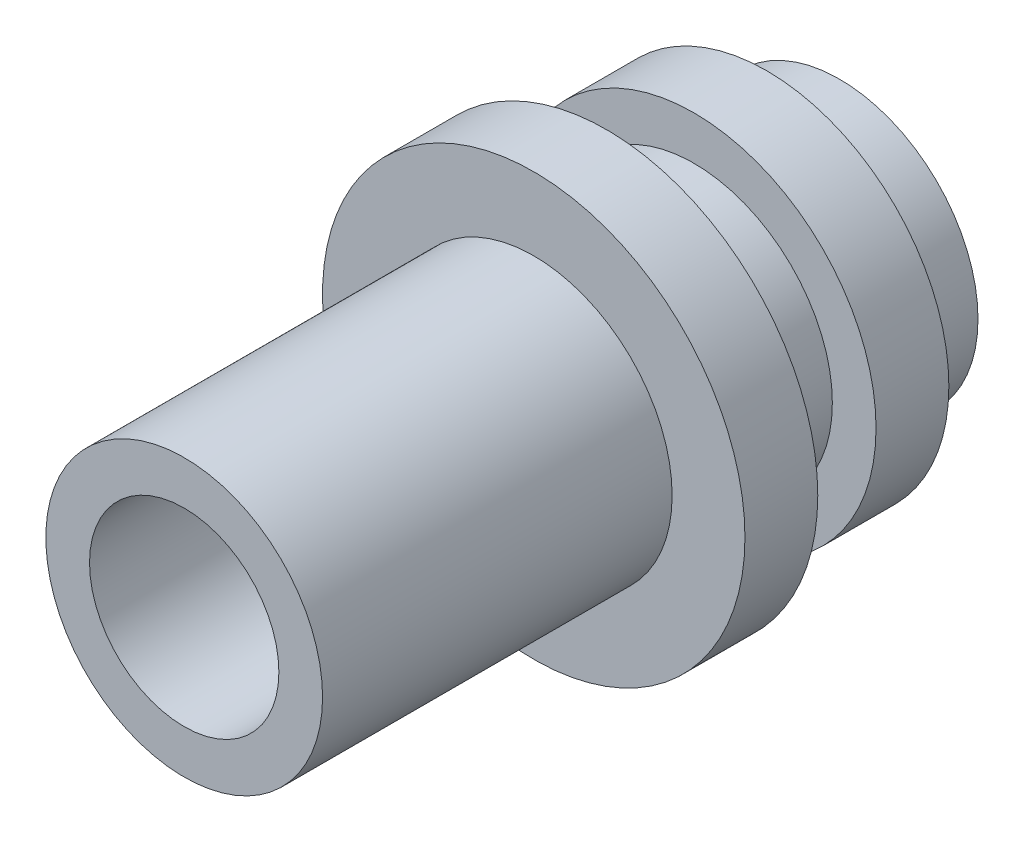
SolidWorks part; units mm, degrees
material "Brass"
ref_plane "Front Plane" through (0, 0, 0) normal (0, 0, 1) x (1, 0, 0)
ref_plane "Top Plane" through (0, 0, 0) normal (0, 1, 0) x (1, 0, 0)
ref_plane "Right Plane" through (0, 0, 0) normal (1, 0, 0) x (0, 0, -1)
other "Configuration Table"
sketch "Sketch1" plane through (0, 0, 0) normal (0, 0, 1) x (1, 0, 0)
  circle A0 centre (0, 0) radius 7.25
  dimension "D1" = 14.5
extrude "Flange" add sketch "Sketch1" along normal blind 2.5
sketch "Sketch2" plane through (0, 0, 0) normal (0, 0, 1) x (1, 0, 0)
  circle A0 centre (0, 0) radius 4.75
  dimension "D1" = 9.5
extrude "Barrel" add sketch "Sketch2" along normal blind 12 from offset 2.5
sketch "Sketch3" plane through (0, 0, 0) normal (0, 0, 1) x (1, 0, 0)
  circle A0 centre (0, 0) radius 4.75
  dimension "D1" = 9.5
extrude "Rear_Thread" add sketch "Sketch3" along normal blind 8 from offset 8
sketch "Sketch4" plane through (0, 0, 0) normal (0, 0, 1) x (1, 0, 0)
  circle A0 centre (0, 0) radius 6.25
  dimension "D1" = 12.5
extrude "Rear_Nut" add sketch "Sketch4" along normal blind 2.5 from offset 5.5
sketch "Sketch5" plane through (0, 0, 0) normal (0, 0, 1) x (1, 0, 0)
  circle A0 centre (0, 0) radius 3.25
  dimension "D1" = 6.5
extrude "Socket_Bore" cut sketch "Sketch5" against normal blind 8 from offset 14.5
equation "\"Jar_OD\"= 90  'ASSUMED - Part G fallback - jar outer diameter"
equation "\"Jar_H\"= 120  'ASSUMED - Part G fallback - jar height"
equation "\"Pump_L\"= 45  'ASSUMED - Part G fallback"
equation "\"Pump_W\"= 24  'ASSUMED - Part G fallback"
equation "\"Pump_H\"= 33  'ASSUMED - Part G fallback"
equation "\"Pump_Outlet_OD\"= 7.5  'ASSUMED - Part G fallback"
equation "\"Tube_OD\"= 8  'ASSUMED - Part G fallback"
equation "\"Tube_ID\"= 6  'ASSUMED - Part G fallback"
equation "\"TDS_Body_Dia\"= 12  'ASSUMED - Part G fallback"
equation "\"TDS_Wet_Len\"= 45  'ASSUMED - Part G fallback - length in water"
equation "\"DS_Tube_Dia\"= 6  'ASSUMED - Part G fallback"
equation "\"DS_Tube_Len\"= 50  'ASSUMED - Part G fallback"
equation "\"ORP_Body_Dia\"= 12  'ASSUMED - Part G fallback"
equation "\"ORP_Body_Len\"= 150  'ASSUMED - Part G fallback"
equation "\"ORP_Cap_Dia\"= 16  'ASSUMED - Part G fallback"
equation "\"Turb_W\"= 33  'ASSUMED - Part G fallback - head width"
equation "\"Turb_D\"= 28  'ASSUMED - Part G fallback - head depth"
equation "\"Turb_H\"= 30  'ASSUMED - Part G fallback - head height"
equation "\"Turb_Slot_W\"= 10  'ASSUMED - Part G fallback - slot width"
equation "\"Flow_L\"= 62  'ASSUMED - Part G fallback YF-S201"
equation "\"Flow_W\"= 36  'ASSUMED - Part G fallback"
equation "\"Flow_H\"= 35  'ASSUMED - Part G fallback"
equation "\"Thread_G12_OD\"= 20.955  'ASSUMED - Part G fallback thread G1/2 (major diameter)"
equation "\"Valve_L\"= 75  'ASSUMED - Part G fallback"
equation "\"Valve_W\"= 45  'ASSUMED - Part G fallback"
equation "\"Valve_H\"= 60  'ASSUMED - Part G fallback"
equation "\"Tee_L\"= 40  'ASSUMED - Part G fallback - overall length"
equation "\"Tee_Branch_L\"= 25  'ASSUMED - Part G fallback"
equation "\"Tee_OD\"= 12  'ASSUMED - Part G fallback"
equation "\"Cuv_W\"= 12.5  'ASSUMED - old R3 cuvette (station suppressed in SS4)"
equation "\"Cuv_D\"= 12.5  'ASSUMED - old R3 cuvette (station suppressed in SS4)"
equation "\"Cuv_H\"= 45  'ASSUMED - old R3 cuvette (station suppressed in SS4)"
equation "\"LED_Board_L\"= 20  'ASSUMED - Part G fallback"
equation "\"LED_Board_W\"= 20  'ASSUMED - Part G fallback - LED at centre"
equation "\"GUVA_L\"= 20  'ASSUMED - Part G fallback"
equation "\"GUVA_W\"= 12  'ASSUMED - Part G fallback - sensor at centre"
equation "\"Reed_L\"= 27  'ASSUMED - Part G fallback MC-38 half"
equation "\"Reed_W\"= 14  'ASSUMED - Part G fallback"
equation "\"Reed_H\"= 8  'ASSUMED - Part G fallback"
equation "\"ESP_L\"= 51  'ASSUMED - Part G fallback"
equation "\"ESP_W\"= 28  'ASSUMED - Part G fallback"
equation "\"TFT_L\"= 58  'ASSUMED - Part G fallback - board"
equation "\"TFT_W\"= 35  'ASSUMED - Part G fallback - board"
equation "\"TFT_Win_L\"= 35  'ASSUMED - Part G fallback - visible window"
equation "\"TFT_Win_W\"= 28  'ASSUMED - Part G fallback - visible window"
equation "\"Relay_L\"= 50  'ASSUMED - Part G fallback"
equation "\"Relay_W\"= 26  'ASSUMED - Part G fallback"
equation "\"Relay_H\"= 19  'ASSUMED - Part G fallback"
equation "\"Mosfet_L\"= 34  'ASSUMED - Part G fallback"
equation "\"Mosfet_W\"= 17  'ASSUMED - Part G fallback"
equation "\"Mosfet_H\"= 12  'ASSUMED - Part G fallback"
equation "\"TDS_Board_L\"= 42  'ASSUMED - Part G fallback"
equation "\"TDS_Board_W\"= 32  'ASSUMED - Part G fallback"
equation "\"Turb_Board_L\"= 38  'ASSUMED - Part G fallback"
equation "\"Turb_Board_W\"= 28  'ASSUMED - Part G fallback"
equation "\"BNC_Thread_Dia\"= 9.5  'ASSUMED - Part G fallback"
equation "\"Plate_L\"= 420  'ASSUMED - Part G fallback"
equation "\"Plate_W\"= 297  'ASSUMED - Part G fallback"
equation "\"Plate_T\"= 6  'ASSUMED - Part G fallback"
equation "\"Probe_Clr\"= 0.3  'DESIGN VALUE - Part C rule 3 - printed probe hole = diameter + 0.3"
equation "\"Cuv_Clr\"= 0.2  'DESIGN VALUE - Part C rule 3 - cuvette pocket = size + 0.2"
equation "\"Label_H\"= 0.6  'DESIGN VALUE - Part D - raised label height"
equation "\"D1@Sketch2\" = \"BNC_Thread_Dia\""
equation "\"Booster_L\"= 150  'ASSUMED - Part G fallback - booster pump"
equation "\"Booster_W\"= 95  'ASSUMED - Part G fallback"
equation "\"Booster_H\"= 100  'ASSUMED - Part G fallback"
equation "\"PTube_OD\"= 6.35  'ASSUMED - Part G fallback - product tube 1/4 inch"
equation "\"Qz_Out\"= 12  'ASSUMED - Part G fallback - quartz channel outside square"
equation "\"Qz_Path\"= 10  'ASSUMED - Part G fallback - quartz channel inside light path"
equation "\"Qz_L\"= 40  'ASSUMED - Part G fallback - quartz channel length"
equation "\"LED860_Dia\"= 5  'ASSUMED - Part G fallback - 860 nm LED"
equation "\"BPW_L\"= 5.4  'ASSUMED - Part G fallback - BPW34"
equation "\"BPW_W\"= 4.3  'ASSUMED - Part G fallback - BPW34"
equation "\"Cart_Dia\"= 50  'ASSUMED - Part G fallback - sediment and pre-carbon cartridges"
equation "\"Cart_L\"= 255  'ASSUMED - Part G fallback"
equation "\"UF_Dia\"= 50  'ASSUMED - Part G fallback - UF cartridge"
equation "\"UF_L\"= 260  'ASSUMED - Part G fallback"
equation "\"RO_Dia\"= 62  'ASSUMED - Part G fallback - RO membrane housing"
equation "\"RO_L\"= 300  'ASSUMED - Part G fallback"
equation "\"UVC_Dia\"= 40  'ASSUMED - Part G fallback - UV-C chamber"
equation "\"UVC_L\"= 300  'ASSUMED - Part G fallback"
equation "\"Tank_W\"= 260  'ASSUMED - Part G fallback - storage tank"
equation "\"Tank_D\"= 160  'ASSUMED - Part G fallback"
equation "\"Tank_H\"= 300  'ASSUMED - Part G fallback"
equation "\"Cab_W\"= 400  'ASSUMED - Part G fallback - purifier cabinet"
equation "\"Cab_D\"= 270  'ASSUMED - Part G fallback"
equation "\"Cab_H\"= 560  'ASSUMED - Part G fallback"
equation "\"ORP_Board_L\"= 40  'ASSUMED - Part G fallback - ORP buffer board"
equation "\"ORP_Board_W\"= 30  'ASSUMED - Part G fallback"
equation "\"Opt_Board_L\"= 50  'ASSUMED - Part G fallback - optical front-end board"
equation "\"Opt_Board_W\"= 40  'ASSUMED - Part G fallback"
equation "\"Buck_L\"= 43  'ASSUMED - Part G fallback - 12 V to 5 V buck module"
equation "\"Buck_W\"= 21  'ASSUMED - Part G fallback"
equation "\"Buck_H\"= 14  'ASSUMED - Part G fallback"
equation "\"BB_L\"= 165  'ASSUMED - Part G fallback - breadboard (As_Built_R3 only)"
equation "\"BB_W\"= 55  'ASSUMED - Part G fallback"
equation "\"BB_H\"= 10  'ASSUMED - Part G fallback"
